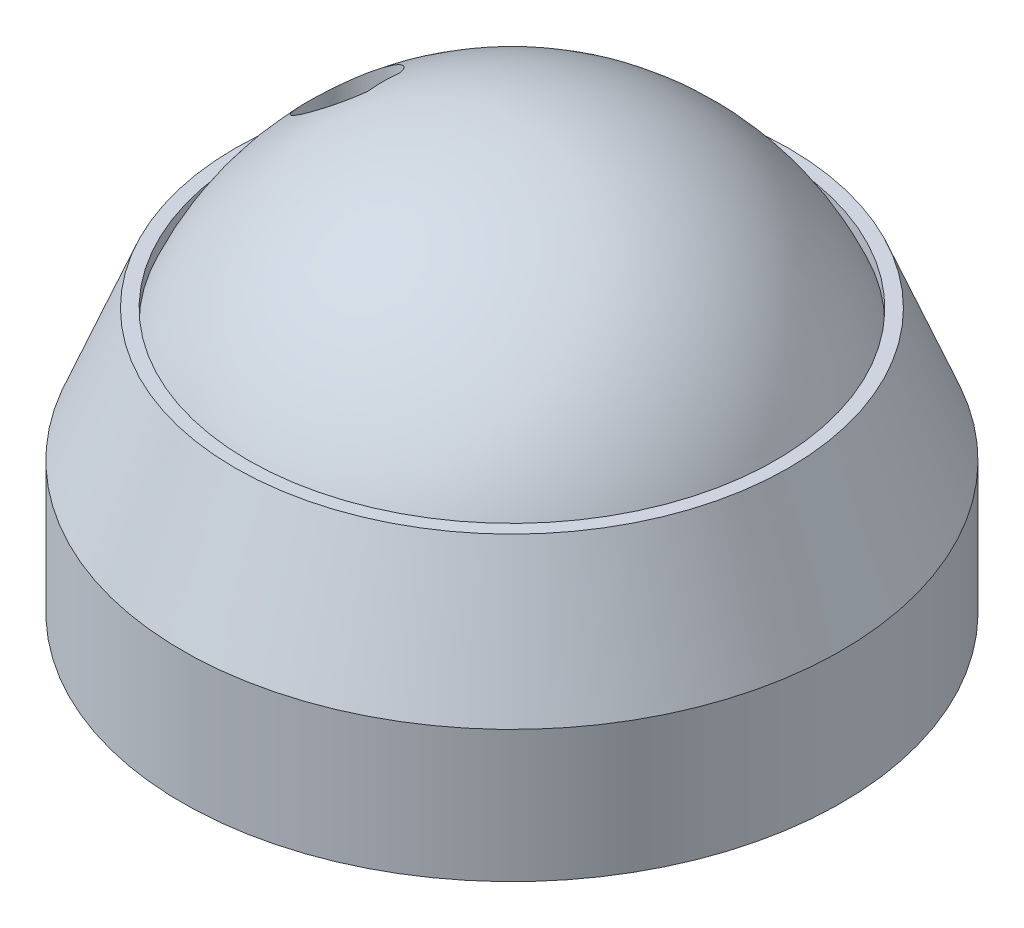
SolidWorks part; units mm, degrees
ref_plane "Plan de face" through (0, 0, 0) normal (0, 0, 1) x (1, 0, 0)
ref_plane "Plan de dessus" through (0, 0, 0) normal (0, 1, 0) x (1, 0, 0)
ref_plane "Plan de droite" through (0, 0, 0) normal (1, 0, 0) x (0, 0, -1)
sketch "Esquisse2" plane through (0, 0, 0) normal (0, 0, 1) x (1, 0, 0)
  line L0 (0, 0) -> (37.5, 0)
  line L1 (37.5, 0) -> (37.5, 15)
  line L2 (37.5, 15) -> (31.5, 30)
  line L3 (31.5, 30) -> (31.5, 0)
  line L4 (31.5, 30) -> (30, 30)
  line L5 (30, 30) -> (30, 28.5)
  line L6 (0, 0) -> (0, 48.5)
  line L7 (30, 30) -> (31.5, 30)
  arc A0 (0, 48.5) -> (30, 28.5) centre (0, 16) cw
  dimension "D1" = 15
  dimension "D2" = 1.5
  dimension "D3" = 1.5
  dimension "D4" = 37.5
  dimension "D5" = 20
  dimension "D6" = 15
  dimension "D7" = 6
revolve "Révolution1" add sketch "Esquisse2" angle 360 about L6
scale "Echelle1" scale about origin uniform scaling yes scale factor 0.6
sketch "Esquisse3" plane through (0, 0, 0) normal (0, -1, 0) x (-1, 0, 0)
  circle A0 centre (0, 0) radius 7.5
  dimension "D1" = 15
extrude "Boss.-Extru.1" add sketch "Esquisse3" along normal blind 10
sketch "Esquisse4" plane through (0, 0, 0) normal (0, -1, 0) x (-1, 0, 0)
  line L0 (20.7981, 0) -> (-19.8566, 0) construction
  circle A0 centre (0, 0) radius 11.25 construction
  circle A1 centre (11.25, 0) radius 2.75
  dimension "D1" = 22.5
  dimension "D2" = 5.5
extrude "Enlèv. mat.-Extru.1" cut sketch "Esquisse4" against normal blind 27
